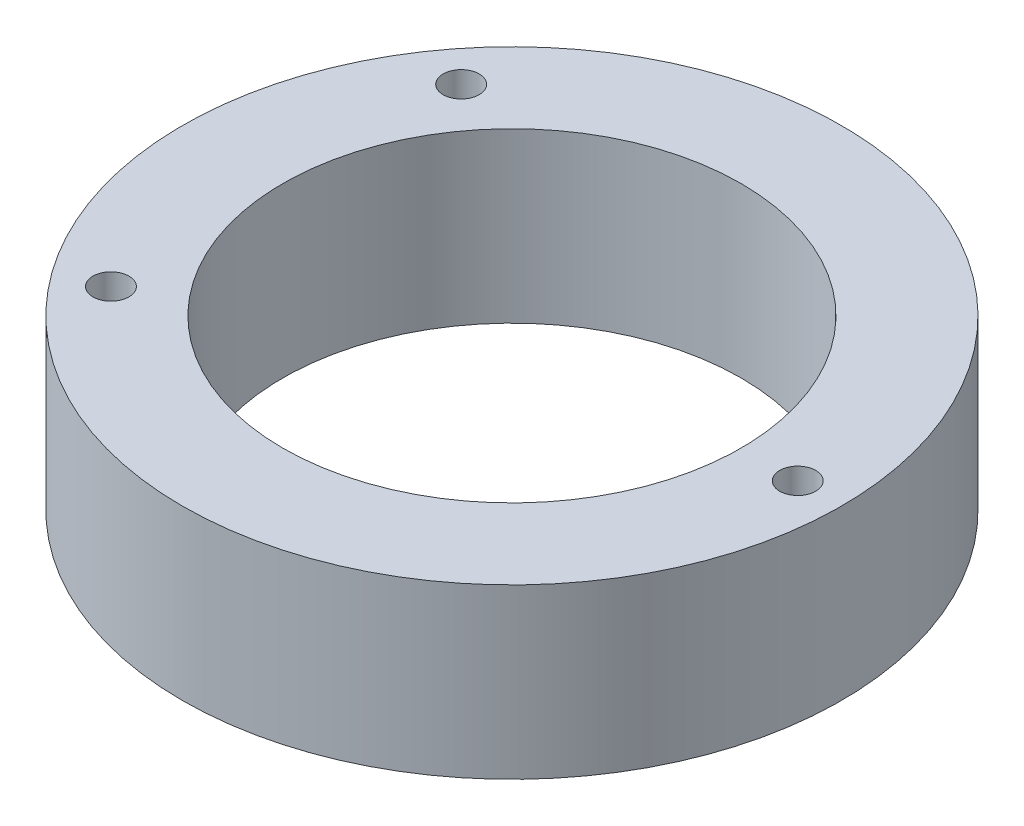
SolidWorks part; units mm, degrees
ref_plane "Front Plane" through (0, 0, 0) normal (0, 0, 1) x (1, 0, 0)
ref_plane "Top Plane" through (0, 0, 0) normal (0, 1, 0) x (1, 0, 0)
ref_plane "Right Plane" through (0, 0, 0) normal (1, 0, 0) x (0, 0, -1)
sketch "Sketch1" plane through (0, 0, 0) normal (0, 1, 0) x (1, 0, 0)
  line L0 (0, 0) -> (-21.9313, 17.0024) construction
  line L1 (0, 0) -> (-21.9313, -17.0024) construction
  line L2 (0, 0) -> (27.75, 0) construction
  line L3 (-21.9313, 17.0024) -> (-21.9313, -17.0024) construction
  circle A0 centre (0, 0) radius 22.25
  circle A1 centre (0, 0) radius 32
  circle A2 centre (27.75, 0) radius 1.75
  circle A3 centre (-21.9313, 17.0024) radius 1.75
  circle A4 centre (-21.9313, -17.0024) radius 1.75
  dimension "D1" = 44.5
  dimension "D2" = 64
  dimension "D5" = 3.5
  dimension "D3" = 75.57
  dimension "D4" = 27.75
extrude "Boss-Extrude1" add sketch "Sketch1" along normal blind 13 and the other way blind 3.35
